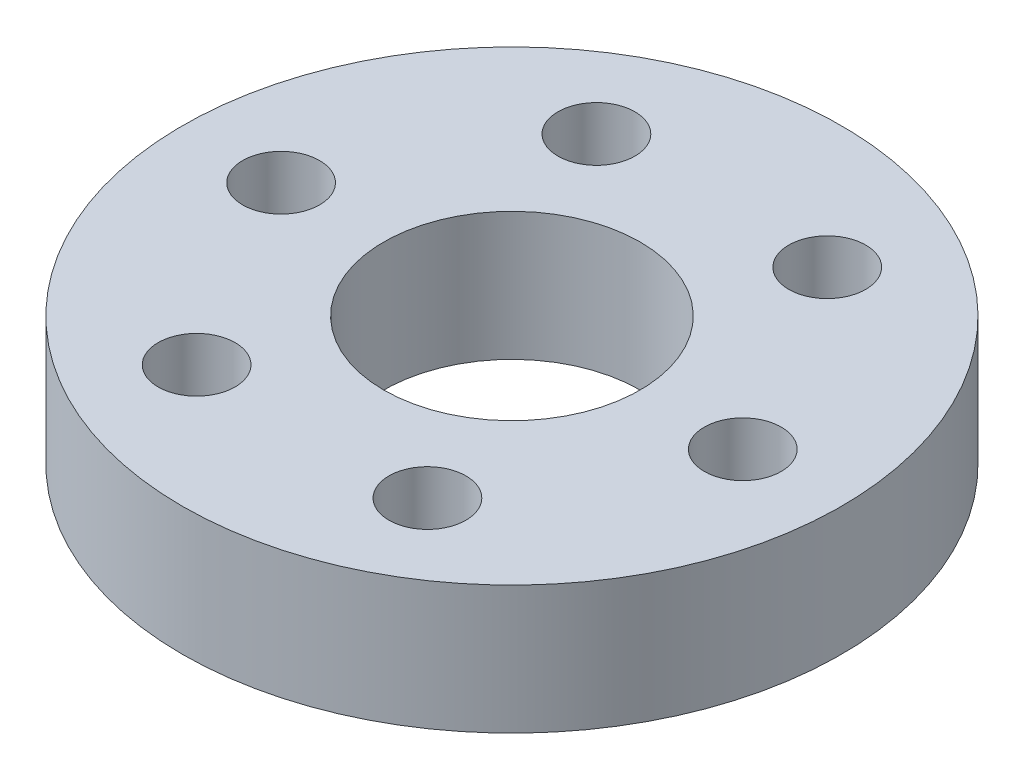
SolidWorks part; units mm, degrees
material "E-Glass Fiber"
ref_plane "Front Plane" through (0, 0, 0) normal (0, 0, 1) x (1, 0, 0)
ref_plane "Top Plane" through (0, 0, 0) normal (0, 1, 0) x (1, 0, 0)
ref_plane "Right Plane" through (0, 0, 0) normal (1, 0, 0) x (0, 0, -1)
sketch "Sketch1" plane through (0, 0, 0) normal (0, 1, 0) x (1, 0, 0)
  line L0 (0, 0) -> (-20.5384, 0) construction
  line L1 (0, 0) -> (7.6387, 13.2306) construction
  line L2 (0, 0) -> (8.8584, -15.3431) construction
  circle A0 centre (0, 0) radius 12.85
  circle A1 centre (4.5, 7.7942) radius 1.5
  circle A2 centre (-9, 0) radius 1.5
  circle A3 centre (4.5, -7.7942) radius 1.5
  circle A4 centre (0, 0) radius 5
  circle A5 centre (-9, 0) radius 3 construction
  point P6 (-9, 0)
  point P7 (4.5, 7.7942)
  point P8 (4.5, -7.7942)
  dimension "D1" = 25.7
  dimension "D7" = 3
  dimension "D8" = 3
  dimension "D9" = 3
  dimension "D10" = 10
  dimension "D11" = 6
  dimension "D2" = 120
  dimension "D3" = 120
  dimension "D4" = 9
  dimension "D5" = 9
  dimension "D6" = 9
extrude "Boss-Extrude1" add sketch "Sketch1" along normal blind 5
sketch "Sketch2" plane through (0, 5, 0) normal (0, 1, 0) x (1, 0, 0)
  line L0 (0, 0) -> (15.2437, 0) construction
  line L1 (0, 0) -> (-7.9898, 13.8388) construction
  line L2 (0, 0) -> (-7.437, -12.8813) construction
  circle A0 centre (-4.5, 7.7942) radius 3 construction
  point P5 (9, 0)
  point P6 (-4.5, 7.7942)
  point P7 (-4.5, -7.7942)
  dimension "D6" = 6
  dimension "D1" = 120
  dimension "D2" = 120
  dimension "D3" = 9
  dimension "D4" = 9
  dimension "D5" = 9
hole_wizard "Ø6.0mm Dowel Hole1" positions "Sketch4" profile "Sketch3" hole size "Ø6.0" standard "ANSI Metric" end condition up to next
sketch "Sketch4" plane through (0, 5, 0) normal (0, 1, 0) x (1, 0, 0)
  point P0 (9, 0)
  point P3 (-4.5, 7.7942)
  point P6 (-4.5, -7.7942)
sketch "Sketch3" plane through (9, 5, 0) normal (1, 0, 0) x (0, 0, 1)
  line L0 (0, 0) -> (0, 5)
  line L1 (0, 5) -> (1.5, 5)
  line L2 (1.5, 5) -> (1.5, 0)
  line L5 (1.5, 0) -> (0, 0)
  line L11 (0, -6.35) -> (0, 107.95) construction
  dimension "Thru Hole Dia." = 3
  dimension "Thru Hole Depth" = 5
